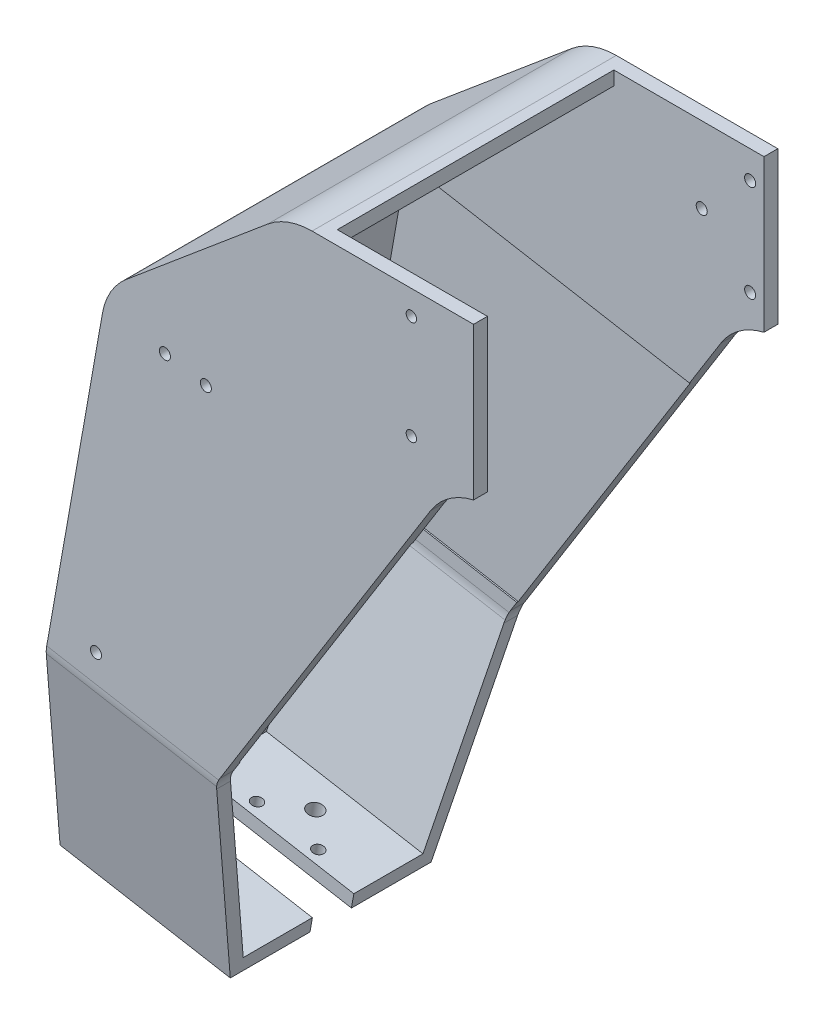
SolidWorks part; units mm, degrees
ref_plane "前视基准面" through (0, 0, 0) normal (0, 0, 1) x (1, 0, 0)
ref_plane "上视基准面" through (0, 0, 0) normal (0, 1, 0) x (1, 0, 0)
ref_plane "右视基准面" through (0, 0, 0) normal (1, 0, 0) x (0, 0, -1)
other "Configuration Table"
sketch "草图1" plane through (0, 0, 0) normal (0, 0, 1) x (1, 0, 0)
  line L0 (20.6573, 53.6387) -> (44.0176, 53.6387)
  line L1 (14.2295, 51.2992) -> (-6.2397, 34.1235)
  line L2 (-9.6599, 28.1995) -> (-22.9197, -47.0007)
  line L3 (44.0176, 53.6387) -> (44.0176, 51.6387)
  line L4 (44.0176, 51.6387) -> (21.3853, 51.6387)
  line L5 (14.9574, 49.2992) -> (-4.3965, 33.0593)
  line L7 (-22.9197, -47.0007) -> (-20.9501, -47.348)
  line L8 (-7.8167, 27.1354) -> (-20.9501, -47.348)
  arc A0 (-9.6599, 28.1995) -> (-6.2397, 34.1235) centre (0.1882, 26.4631) cw
  arc A1 (14.2295, 51.2992) -> (20.6573, 53.6387) centre (20.6573, 43.6387) cw
  arc A2 (-7.8167, 27.1354) -> (-4.3965, 33.0593) centre (2.0314, 25.3989) cw
  arc A3 (14.9574, 49.2992) -> (21.3853, 51.6387) centre (21.3853, 41.6387) cw
  point P6 (-9.0279, 31.7839)
  point P9 (17.0176, 53.6387)
  dimension "D6" = 10
  dimension "D9" = 10
  dimension "D1" = 140
  dimension "D2" = 34
  dimension "D3" = 27
  dimension "D4" = 140
  dimension "D5" = 80
  dimension "D7" = 2
  dimension "D8" = 2
extrude "凸台-拉伸1" add sketch "草图1" along normal mid plane 40 contours L4 A3 L5 A2 L8 L7 L2 A0 L1 A1 L0 L3
sketch "草图3" plane through (-14.191, 2.5023, 0) normal (-0.9848, 0.1736, 0) x (0, 0, 1)
  line L0 (13, -50.2666) -> (20, -50.2666)
  line L2 (20, 26.0937) -> (20, -50.2666) construction
  line L3 (20, -20.9063) -> (13, -50.2666)
  line L4 (20, -50.2666) -> (-20, -50.2666) construction
  line L5 (20, -50.2666) -> (20, -20.9063)
  line L6 (20, 26.0937) -> (-20, 26.0937) construction
  dimension "D1" = 47
  dimension "D2" = 7
extrude "切除-拉伸1" cut sketch "草图3" against normal up to surface (2 mm away) contours L3 L0 L5 up to face at (-14.3834, -10.1063, 0)
mirror "镜向1" about plane through (0, 0, 0) normal (0, 0, 1) of "切除-拉伸1"
sketch "草图4" plane through (0, 0, 20) normal (0, 0, 1) x (1, 0, 0)
  line L0 (44.0176, 53.6387) -> (44.0176, 31.6387)
  line L2 (-17.8214, -18.0864) -> (6.7988, -22.4276)
  line L3 (-9.6599, 28.1995) -> (-17.8214, -18.0864) construction
  line L4 (14.2295, 51.2992) -> (-6.2397, 34.1235) construction
  line L5 (20.6573, 53.6387) -> (44.0176, 53.6387) construction
  line L6 (-9.6599, 28.1995) -> (-17.8214, -18.0864)
  line L7 (14.2295, 51.2992) -> (-6.2397, 34.1235)
  line L8 (20.6573, 53.6387) -> (44.0176, 53.6387)
  line L9 (37.8093, 27.1995) -> (6.7988, -22.4276)
  arc A0 (-6.2397, 34.1235) -> (-9.6599, 28.1995) centre (0.1882, 26.4631) ccw construction
  arc A1 (20.6573, 53.6387) -> (14.2295, 51.2992) centre (20.6573, 43.6387) ccw construction
  arc A2 (-6.2397, 34.1235) -> (-9.6599, 28.1995) centre (0.1882, 26.4631) ccw
  arc A3 (20.6573, 53.6387) -> (14.2295, 51.2992) centre (20.6573, 43.6387) ccw
  arc A4 (37.8093, 27.1995) -> (44.0176, 31.6387) centre (46.2898, 21.9003) cw
  dimension "D1" = 22
  dimension "D3" = 25
extrude "凸台-拉伸2" add sketch "草图4" along normal blind 2
sketch "草图5" plane through (-14.191, 2.5023, 0) normal (-0.9848, 0.1736, 0) x (0, 0, 1)
  line L0 (22, -20.9063) -> (15, -50.2666)
  line L1 (20, -20.9063) -> (13, -50.2666) construction
  line L3 (22, -20.9063) -> (20, -20.9063) construction
  line L4 (20, -20.9063) -> (13, -50.2666)
  line L5 (22, -20.9063) -> (20, -20.9063)
  line L6 (13, -50.2666) -> (15, -50.2666)
extrude "凸台-拉伸3" add sketch "草图5" against normal blind 33
mirror "镜向3" about plane through (0, 0, 0) normal (0, 0, 1) of "凸台-拉伸3", "凸台-拉伸2"
sketch "草图18" plane through (0, 0, 0) normal (0, 0, 1) x (1, 0, 0)
  line L9 (6.7988, -22.4276) -> (1.7005, -51.3419)
  line L10 (-22.9197, -47.0007) -> (-17.8214, -18.0864) construction
  line L11 (6.7988, -22.4276) -> (14.6773, -23.8168)
  line L12 (14.6773, -23.8168) -> (9.5789, -52.7311)
  line L13 (9.5789, -52.7311) -> (1.7005, -51.3419)
extrude "切除-拉伸10" cut sketch "草图18" against normal mid plane 45
sketch "草图10" plane through (-14.191, 2.5023, 0) normal (-0.9848, 0.1736, 0) x (0, 0, 1)
  line L0 (-15, -50.2666) -> (15, -50.2666)
  line L1 (-14.5232, -52.2666) -> (14.5232, -52.2666)
  line L2 (15, -50.2666) -> (14.5232, -52.2666)
  line L4 (-15, -50.2666) -> (-14.5232, -52.2666)
  line L6 (15, -50.2666) -> (22, -20.9063) construction
  line L7 (-15, -50.2666) -> (-22, -20.9063) construction
  dimension "D1" = 2
extrude "凸台-拉伸4" add sketch "草图10" against normal up to surface (25 mm away) up to face at (4.2497, -36.8848, 17.5)
sketch "草图19" plane through (-14.191, 2.5023, 0) normal (-0.9848, 0.1736, 0) x (0, 0, 1)
  line L0 (-14.5232, -52.2666) -> (14.5232, -52.2666) construction
  line L1 (-3, -30.2666) -> (3, -30.2666)
  line L2 (-3, -30.2666) -> (-3, -52.2666)
  line L3 (-3, -52.2666) -> (3, -52.2666)
  line L4 (3, -30.2666) -> (3, -52.2666)
  line L5 (0, -37.0066) -> (0, 37.0066) construction
  dimension "D1" = 3
  dimension "D2" = 3
  dimension "D3" = 22
extrude "切除-拉伸11" cut sketch "草图19" against normal through all
sketch "草图15" plane through (0, 0, 22) normal (0, 0, 1) x (1, 0, 0)
  line L0 (44.0176, 31.6387) -> (44.0176, 53.6387) construction
  line L1 (44.0176, 53.6387) -> (20.6573, 53.6387) construction
  line L2 (35.0176, 54.6473) -> (35.0176, 19.8627) construction
  circle A0 centre (35.0176, 50.1387) radius 0.75
  circle A1 centre (35.0176, 35.1387) radius 0.75
  dimension "D1" = 9
  dimension "D2" = 3.5
  dimension "D3" = 15
extrude "切除-拉伸7" cut sketch "草图15" against normal up to next
sketch "草图16" plane through (0, 0, -22) normal (0, 0, -1) x (-1, 0, 0)
  line L0 (-44.0176, 53.6387) -> (-20.6573, 53.6387) construction
  line L1 (-44.0176, 31.6387) -> (-44.0176, 53.6387) construction
  circle A0 centre (-42.0176, 49.6387) radius 0.8
  circle A1 centre (-42.0176, 35.6387) radius 0.8
  circle A2 centre (-35.0176, 42.6387) radius 0.8
  dimension "D1" = 4
  dimension "D2" = 2
  dimension "D3" = 14
  dimension "D4" = 7
  dimension "D5" = 7
extrude "切除-拉伸8" cut sketch "草图16" against normal up to next
sketch "草图17" plane through (0, 51.6387, 0) normal (0, -1, 0) x (1, 0, 0)
  line L10 (44.0176, 20) -> (22.3041, 20)
  line L11 (6.7988, 20) -> (37.8093, 20) construction
  line L12 (22.3041, 20) -> (22.3041, -20)
  line L13 (44.0176, -20) -> (21.3853, -20) construction
  line L14 (22.3041, -20) -> (44.0176, -20)
  line L16 (44.0176, 20) -> (44.0176, -20)
extrude "切除-拉伸9" cut sketch "草图17" against normal up to next
sketch "草图23" plane through (0, 0, 22) normal (0, 0, 1) x (1, 0, 0)
  line L0 (-9.4824, 29.2061) -> (17.6755, 24.4174) construction
  line L1 (-9.6599, 28.1995) -> (-17.8214, -18.0864) construction
  circle A0 centre (-0.6191, 27.6432) radius 0.8
  circle A1 centre (5.2897, 26.6013) radius 0.8
  dimension "D2" = 9
  dimension "D1" = 1.75
  dimension "D3" = 6
extrude "切除-拉伸13" cut sketch "草图23" against normal up to next
sketch "草图24" plane through (0, 0, 22) normal (0, 0, 1) x (1, 0, 0)
  line L0 (-7.8167, 27.1354) -> (-15.8517, -18.4337) construction
  line L1 (-17.8214, -18.0864) -> (6.7988, -22.4276) construction
  circle A0 centre (-10.5958, -14.7708) radius 0.8
  dimension "D1" = 4.54
  dimension "D2" = 4.52
extrude "切除-拉伸14" cut sketch "草图24" against normal through all contours A0
sketch "草图25" plane through (-12.2214, 2.155, 0) normal (0.9848, -0.1736, 0) x (0, 0, -1)
  line L0 (13, -50.2666) -> (3, -50.2666) construction
  line L1 (3, -30.2666) -> (7, -30.2666)
  line L2 (3, -30.2666) -> (3, -50.2666)
  line L3 (3, -50.2666) -> (7, -50.2666)
  line L4 (7, -30.2666) -> (7, -50.2666)
  dimension "D1" = 4
extrude "切除-拉伸15" cut sketch "草图25" against normal through all
sketch "草图26" plane through (-9.076, -51.4725, 0) normal (-0.1736, -0.9848, 0) x (0.9848, -0.1736, 0)
  line L0 (-14.4099, -4.75) -> (10.5901, -4.75) construction
  line L1 (-14.4099, -14.5232) -> (-14.4099, -3) construction
  line L2 (10.5901, -3) -> (10.5901, -14.5232) construction
  line L3 (-14.4099, -3) -> (10.5901, -3) construction
  line L4 (-0.9099, -3) -> (-0.9099, -7.7522) construction
  circle A0 centre (3.5901, -4.75) radius 0.8
  circle A1 centre (-5.4099, -4.75) radius 0.8
  dimension "D3" = 4.5
  dimension "D4" = 9
  dimension "D1" = 1.75
  dimension "D2" = 11.5
extrude "切除-拉伸16" cut sketch "草图26" against normal up to next
sketch "草图27" plane through (-9.076, -51.4725, 0) normal (-0.1736, -0.9848, 0) x (0.9848, -0.1736, 0)
  line L0 (-5.4099, -4.75) -> (3.5901, -4.75) construction
  line L1 (-0.9099, -4.75) -> (-0.9099, -10.347) construction
  circle A0 centre (-0.9099, -8.75) radius 1.1
  dimension "D1" = 4
extrude "切除-拉伸17" cut sketch "草图27" against normal up to next
fillet "圆角1" radius 5 2 edges at (-5.5113, -20.257, 22) (-5.5113, -20.257, -22)
fillet "圆角2" radius 5 2 edges at (-4.5265, -20.4307, -20) (-4.5265, -20.4307, 20)
fillet "圆角3" radius 5 10 edges at (6.7988, -22.4276, 20.9653) (6.9665, -22.1593, 21.9913) (6.7489, -22.7106, 21.9228) (6.7988, -22.4276, -20.9653) (6.7489, -22.7106, -21.9228) (6.9665, -22.1593, -21.9913) (6.9665, -22.1593, -19.9913) (6.7489, -22.7106, -19.9228) (6.7489, -22.7106, 19.9228) (6.9665, -22.1593, 19.9913)
sketch "草图28" plane through (0, 0, 0) normal (0, 0, 1) x (1, 0, 0)
  line L0 (-15.4024, -15.8852) -> (-7.8167, 27.1354)
  line L1 (-7.8167, 27.1354) -> (-15.7497, -17.8548) construction
  line L2 (-7.8167, 27.1354) -> (37.1889, 19.1997)
  line L3 (37.1889, 19.1997) -> (27.3985, -23.4322)
  line L4 (27.3985, -23.4322) -> (-15.4024, -15.8852)
  line L5 (-17.7193, -17.5076) -> (7.1466, -21.8921) construction
  dimension "D1" = 2
extrude "切除-拉伸18" cut sketch "草图28" against normal mid plane 40.4 contours L3 L4 L0 L2
